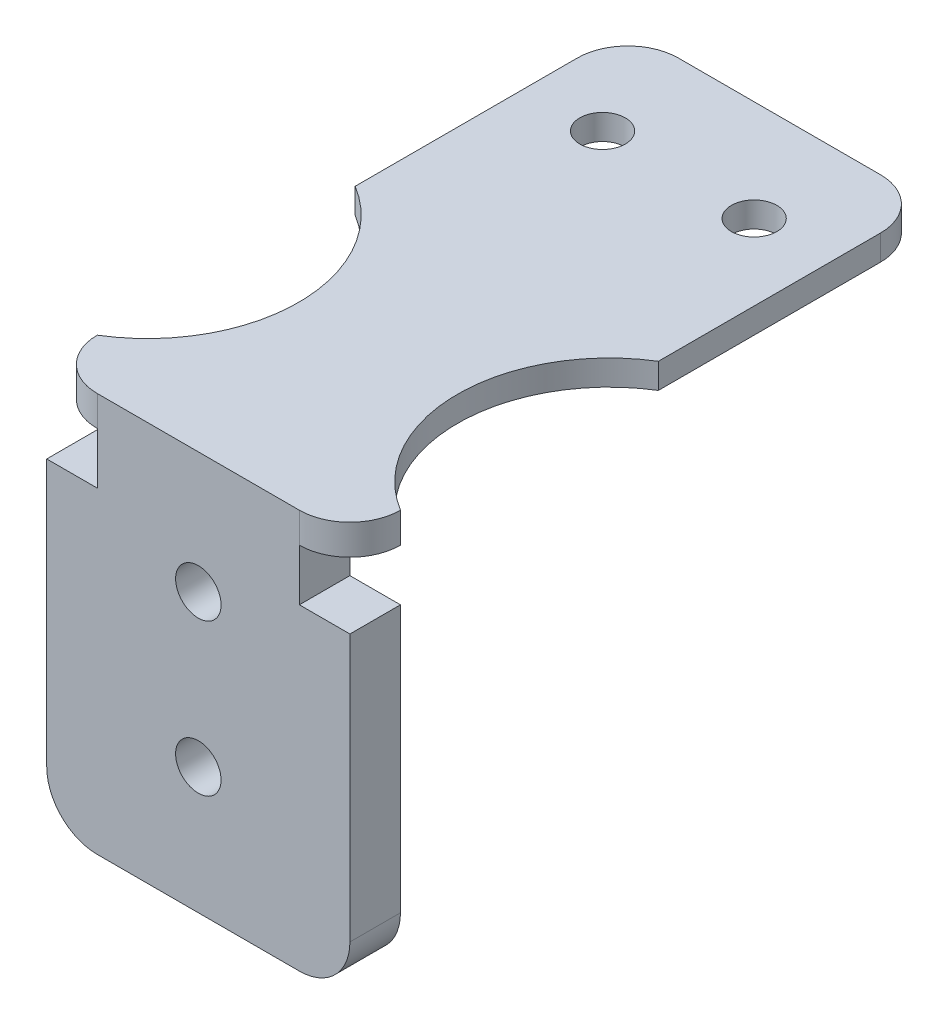
SolidWorks part; units mm, degrees
ref_plane "Front Plane" through (0, 0, 0) normal (0, 0, 1) x (1, 0, 0)
ref_plane "Top Plane" through (0, 0, 0) normal (0, 1, 0) x (1, 0, 0)
ref_plane "Right Plane" through (0, 0, 0) normal (1, 0, 0) x (0, 0, -1)
sketch "Sketch1" plane through (0, 0, 0) normal (0, 1, 0) x (1, 0, 0)
  line L5 (15, 21.25) -> (15, -0.7258)
  line L6 (-15, 21.25) -> (-15, -0.7258)
  line L10 (-15, -26.25) -> (15, -26.25)
  line L13 (-10, 26.25) -> (10, 26.25)
  circle A0 centre (-7.5, 16.25) radius 2.25
  circle A1 centre (7.5, 16.25) radius 2.25
  arc A6 (10, 26.25) -> (15, 21.25) centre (10, 21.25) cw
  arc A7 (-15, 21.25) -> (-10, 26.25) centre (-10, 21.25) cw
  arc A8 (-15, -26.25) -> (-15, -0.7258) centre (-22.8051, -13.4879) ccw
  arc A9 (15, -26.25) -> (15, -0.7258) centre (22.8864, -13.4879) cw
  point P0 (0, 0)
  dimension "D3" = 4.5
  dimension "D4" = 4.5
  dimension "D6" = 5
  dimension "D2" = 30
  dimension "D5" = 15
  dimension "D7" = 10
extrude "Boss-Extrude1" add sketch "Sketch1" along normal blind 2.5
sketch "Sketch3" plane through (0, 0, 26.25) normal (0, 0, 1) x (1, 0, 0)
  line L0 (-10, 3) -> (10, 3)
  line L3 (-10, -37) -> (10, -37)
  line L7 (-15, -5.6076) -> (-10, -5.6076)
  line L8 (-10, 3) -> (-10, -5.6076)
  line L11 (15, -5.6076) -> (10, -5.6076)
  line L12 (10, 3) -> (10, -5.6076)
  line L13 (15, -5.6076) -> (15, -32)
  line L14 (-15, -32) -> (-15, -5.6076)
  arc A0 (10, -37) -> (15, -32) centre (10, -32) ccw
  arc A1 (-15, -32) -> (-10, -37) centre (-10, -32) ccw
  circle A2 centre (0, -9.5) radius 2.25
  circle A3 centre (0, -24.5) radius 2.25
  point P7 (15, -37)
  dimension "D3" = 5
  dimension "D1" = 4.5
  dimension "D2" = 4.5
extrude "Boss-Extrude2" add sketch "Sketch3" along normal blind 5
sketch "Sketch4" plane through (0, 2.5, 0) normal (0, 1, 0) x (1, 0, 0)
  line L0 (10, -31.25) -> (10, -26.25)
  line L1 (10, -26.25) -> (15, -26.25)
  line L2 (-10, -31.25) -> (-10, -26.25)
  line L3 (-10, -26.25) -> (-15, -26.25)
  arc A0 (-10, -31.25) -> (-15, -26.25) centre (-10, -26.25) cw
  arc A1 (10, -31.25) -> (15, -26.25) centre (10, -26.25) ccw
extrude "Boss-Extrude3" add sketch "Sketch4" against normal blind 3
sketch "Sketch5" plane through (0, 0, 26.25) normal (0, 0, -1) x (-1, 0, 0)
  line L5 (-7.8455, -6.7801) -> (7.8455, -6.7801)
  line L6 (-7.8455, -6.7801) -> (-7.8455, 0)
  line L7 (-7.8455, 0) -> (7.8455, 0)
  line L8 (7.8455, -6.7801) -> (7.8455, 0)
  point P4 (0, -3.39)
extrude "Boss-Extrude4" add sketch "Sketch5" along normal blind 10
sketch "Sketch6" plane through (7.8455, 0, 0) normal (1, 0, 0) x (0, 0, -1)
  line L4 (-26.25, -6.7801) -> (-24.6646, -3.7172)
  line L6 (-26.25, -6.7801) -> (-16.25, -6.7801)
  line L8 (-16.25, -6.7801) -> (-16.25, 0)
  arc A2 (-24.6646, -3.7172) -> (-16.25, 0) centre (-31.8438, 23.917) ccw
extrude "Cut-Extrude1" cut sketch "Sketch6" against normal through all both and the other way through all contours L6 L8 A2 L4
fillet "Fillet3" radius 1 2 edges at (7.8455, -3.39, 26.25) (-7.8455, -3.39, 26.25)
equation "\"n\"=0.8"
